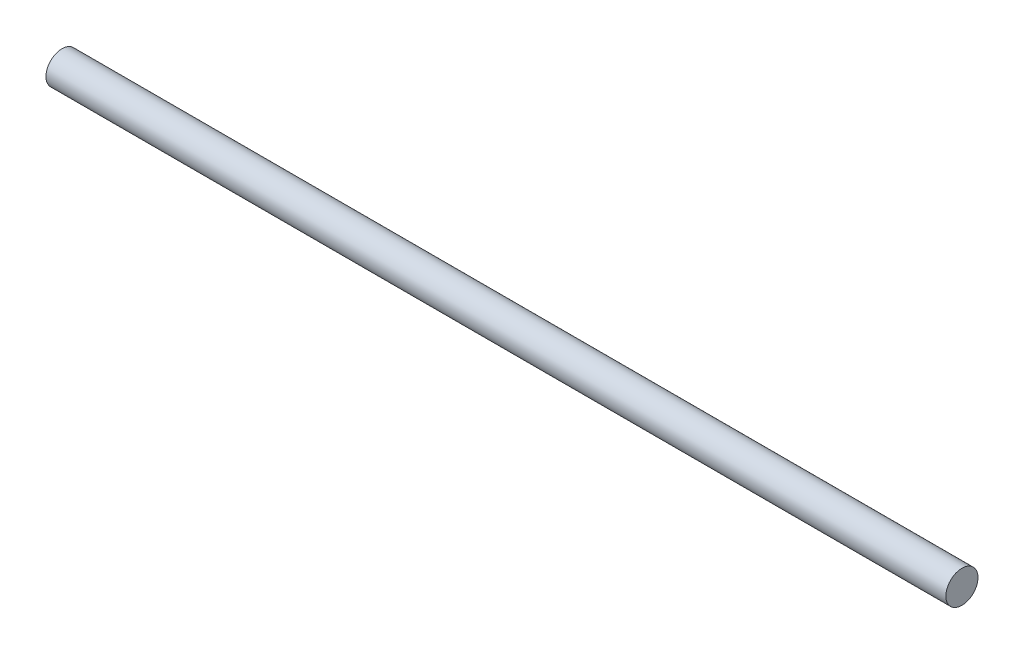
SolidWorks part; units mm, degrees
ref_plane "Front Plane" through (0, 0, 0) normal (0, 0, 1) x (1, 0, 0)
ref_plane "Top Plane" through (0, 0, 0) normal (0, 1, 0) x (1, 0, 0)
ref_plane "Right Plane" through (0, 0, 0) normal (1, 0, 0) x (0, 0, -1)
sketch "Sketch1" plane through (0, 0, 0) normal (1, 0, 0) x (0, 0, -1)
  circle A0 centre (0, 0) radius 2.5
  dimension "D1" = 5
extrude "Boss-Extrude1" add sketch "Sketch1" along normal blind 140
